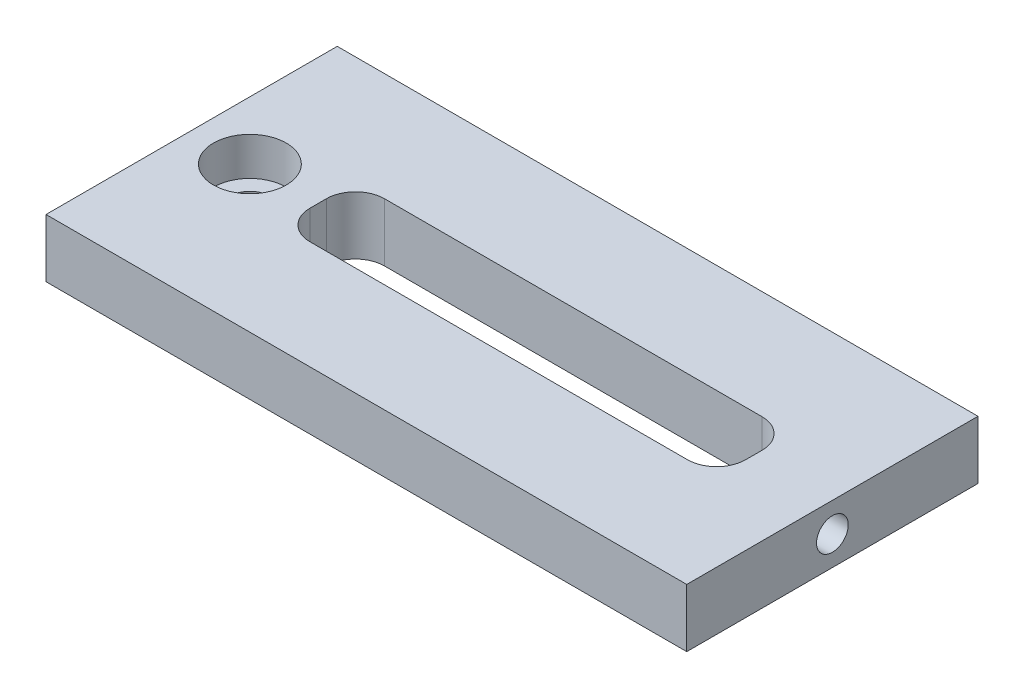
SolidWorks part; units mm, degrees
ref_plane "Front" through (0, 0, 0) normal (0, 0, 1) x (1, 0, 0)
ref_plane "Top" through (0, 0, 0) normal (0, 1, 0) x (1, 0, 0)
ref_plane "Right" through (0, 0, 0) normal (1, 0, 0) x (0, 0, -1)
sketch "Sketch1" plane through (0, 0, 0) normal (0, 1, 0) x (1, 0, 0)
  line L1 (-34.925, -15.875) -> (34.925, -15.875)
  line L2 (-34.925, -15.875) -> (-34.925, 15.875)
  line L3 (-34.925, 15.875) -> (34.925, 15.875)
  line L4 (34.925, -15.875) -> (34.925, 15.875)
  line L5 (-34.925, -15.875) -> (34.925, 15.875) construction
  line L6 (-34.925, 15.875) -> (34.925, -15.875) construction
  point P0 (0, 0)
  dimension "D1" = 69.85
  dimension "D2" = 31.75
extrude "Boss-Extrude1" add sketch "Sketch1" along normal mid plane 6.35 contours L3 L4 L1 L2
sketch "Sketch2" plane through (0, 3.175, 0) normal (0, 1, 0) x (1, 0, 0)
  line L0 (-50, 0) -> (50, 0) construction
  line L4 (-21.1328, -4.064) -> (26.3652, -4.064)
  line L5 (-21.1328, -4.064) -> (-21.1328, 4.064)
  line L6 (-21.1328, 4.064) -> (26.3652, 4.064)
  line L7 (26.3652, -4.064) -> (26.3652, 4.064)
  line L8 (-21.1328, -4.064) -> (26.3652, 4.064) construction
  line L9 (-21.1328, 4.064) -> (26.3652, -4.064) construction
  line L10 (34.925, -15.875) -> (34.925, 15.875) construction
  point P0 (2.6162, 0)
  point P6 (0, 0)
  dimension "D1" = 8.5598
  dimension "D2" = 47.498
  dimension "D3" = 8.128
extrude "Cut-Extrude1" cut sketch "Sketch2" against normal blind 6.35 contours L6 L7 L4 L5
fillet "Fillet1" radius 3.175 4 edges at (26.3652, 0, 4.064) (26.3652, 0, -4.064) (-21.1328, 0, -4.064) (-21.1328, 0, 4.064)
sketch "Sketch3" plane through (0, 3.175, 0) normal (0, 1, 0) x (1, 0, 0)
  line L0 (-50, 0) -> (50, 0) construction
  line L1 (-34.925, -15.875) -> (-34.925, 15.875) construction
  point P0 (-28.575, 0)
  point P1 (0, 0)
  dimension "D1" = 6.35
hole_wizard "CBORE for #8 Socket Head Cap Screw1" positions "Sketch4" profile "Sketch6" counterbore size "#8" standard "ANSI Inch"
sketch "Sketch4" plane through (0, 3.175, 0) normal (0, 1, 0) x (1, 0, 0)
  point P0 (-28.575, 0)
sketch "Sketch6" plane through (-28.575, 3.175, 0) normal (1, 0, 0) x (0, 0, 1)
  line L0 (0, 0) -> (0, 17.8607)
  line L1 (0, 17.8607) -> (2.2479, 16.51)
  line L2 (2.2479, 16.51) -> (2.2479, 4.1656)
  line L3 (2.2479, 4.1656) -> (3.9688, 4.1656)
  line L4 (3.9688, 4.1656) -> (3.9688, 0)
  line L5 (3.9688, 0) -> (0, 0)
  line L10 (0, 17.8607) -> (-2.2479, 16.51) construction
  line L11 (0, -6.35) -> (0, 107.95) construction
  dimension "Hole Dia." = 4.4958
  dimension "Hole Depth" = 16.51
  dimension "C'Bore Dia." = 7.9375
  dimension "C'Bore Depth" = 4.1656
  dimension "Drill Angle" = 118
sketch "Sketch7" plane through (34.925, 0, 0) normal (1, 0, 0) x (0, 0, -1)
  point P0 (0, 0)
hole_wizard "#8-32 Tapped Hole1" positions "Sketch8" profile "Sketch9" tap size "#8-32" standard "ANSI Inch"
sketch "Sketch8" plane through (34.925, 0, 0) normal (1, 0, 0) x (0, 0, -1)
  point P0 (0, 0)
sketch "Sketch9" plane through (34.925, 0, 0) normal (0, 1, 0) x (0, 0, -1)
  line L0 (0, 0) -> (0, 8.5598)
  line L1 (0, 8.5598) -> (1.7272, 8.5598)
  line L2 (1.7272, 8.5598) -> (1.7272, 0)
  line L5 (1.7272, 0) -> (0, 0)
  line L11 (0, -6.35) -> (0, 107.95) construction
  dimension "Thru Tap Drill Dia." = 3.4544
  dimension "Thru Tap Drill Depth" = 8.5598
cosmetic thread "Hole Thread1" parameters "D2"=4.1656
